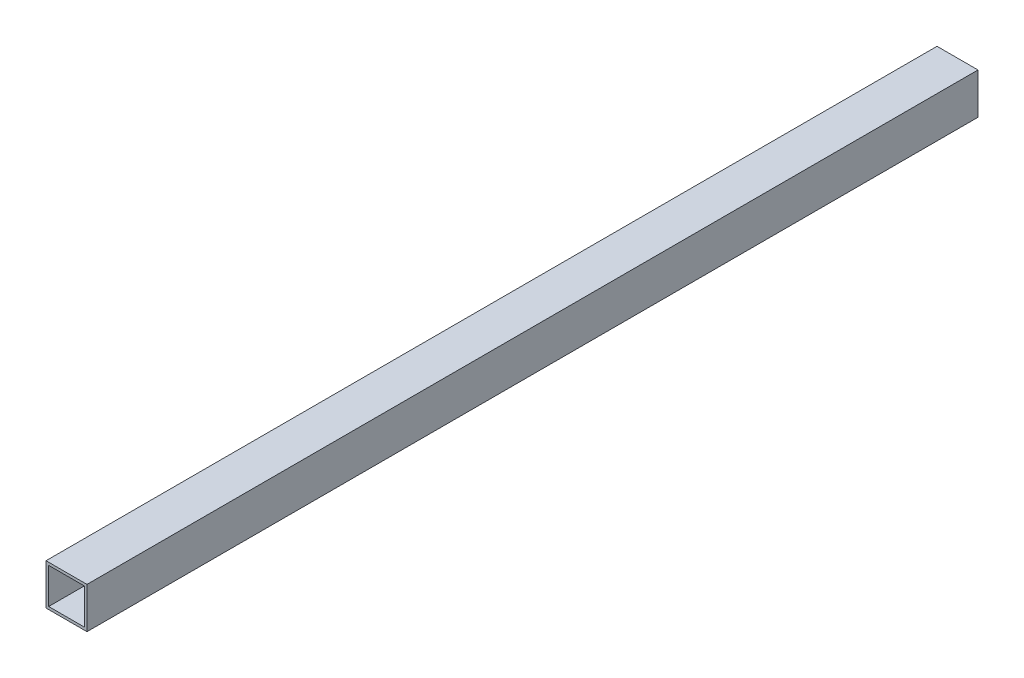
SolidWorks part; units mm, degrees
ref_plane "前视基准面" through (0, 0, 0) normal (0, 0, 1) x (1, 0, 0)
ref_plane "上视基准面" through (0, 0, 0) normal (0, 1, 0) x (1, 0, 0)
ref_plane "右视基准面" through (0, 0, 0) normal (1, 0, 0) x (0, 0, -1)
other "Configuration Table"
sketch "草图1" plane through (0, 0, 0) normal (0, 0, 1) x (1, 0, 0)
  line L0 (-23, 23) -> (23, 23)
  line L1 (-20, -20) -> (20, -20)
  line L2 (-20, -20) -> (-20, 20)
  line L3 (-20, 20) -> (20, 20)
  line L4 (20, -20) -> (20, 20)
  line L5 (-20, -20) -> (20, 20) construction
  line L6 (-20, 20) -> (20, -20) construction
  line L7 (23, -23) -> (23, 23)
  line L8 (-23, -23) -> (23, -23)
  line L9 (-23, -23) -> (-23, 23)
  point P0 (0, 0)
  dimension "D1" = 40
  dimension "D2" = 40
  dimension "D3" = 3
extrude "凸台-拉伸2" add sketch "草图1" along normal blind 1000
